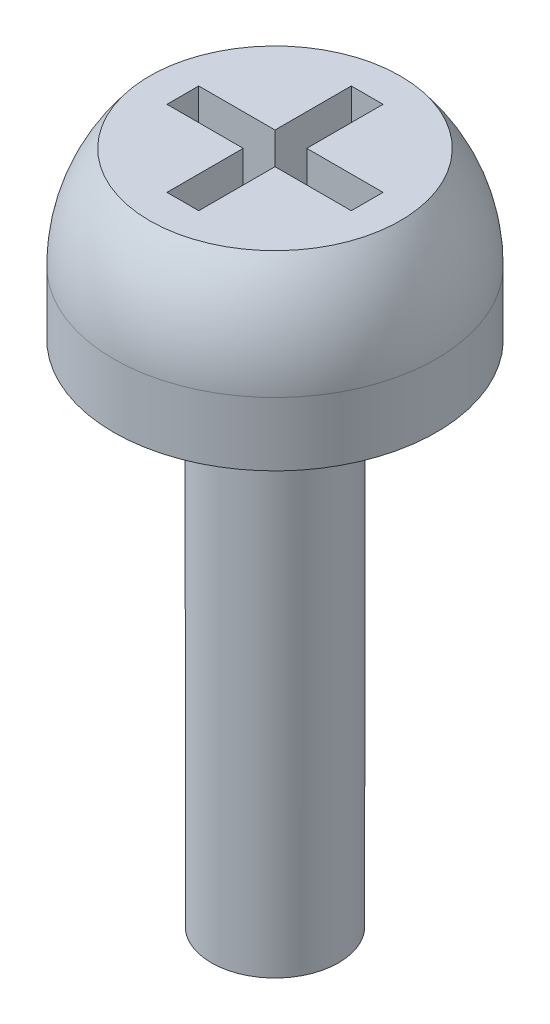
SolidWorks part; units mm, degrees
material "AISI 1020"
ref_plane "Front" through (0, 0, 0) normal (0, 0, 1) x (1, 0, 0)
ref_plane "Top" through (0, 0, 0) normal (0, 1, 0) x (1, 0, 0)
ref_plane "Right" through (0, 0, 0) normal (1, 0, 0) x (0, 0, -1)
sketch "Sketch1" plane through (0, 0, 0) normal (0, 1, 0) x (1, 0, 0)
  circle A0 centre (0, 0) radius 1.27
  dimension "D1" = 2.54
extrude "Boss-Extrude1" add sketch "Sketch1" along normal blind 0.5
ref_plane "Plane1" through (0, 0.5, 0) normal (0, 1, 0) x (1, 0, 0)
sketch "Sketch2" plane through (0, 0.5, 0) normal (0, 1, 0) x (1, 0, 0)
  line L0 (0, 1.27) -> (0, -1.27)
  circle A0 centre (0, 0) radius 1.27 construction
  arc A1 (0, 1.27) -> (0, -1.27) centre (0, 0) ccw
revolve "Revolve1" add sketch "Sketch2" angle 180 about L0
ref_plane "Plane2" through (0, 1.3, 0) normal (0, -1, 0) x (-1, 0, 0)
sketch "Sketch3" plane through (0, 1.3, 0) normal (0, -1, 0) x (-1, 0, 0)
  circle A0 centre (0, 0) radius 2.5
  dimension "D1" = 5
extrude "Cut-Extrude2" cut sketch "Sketch3" against normal blind 1.016
sketch "Sketch5" plane through (0, 1.3, 0) normal (0, -1, 0) x (-1, 0, 0)
  line L0 (0, 0.9864) -> (0, -0.9864) construction
  line L1 (0.9864, 0) -> (-0.9864, 0) construction
  line L2 (0.125, 0.725) -> (0.125, 0.125)
  line L3 (0.125, 0.125) -> (0.725, 0.125)
  line L4 (-0.125, 0.125) -> (-0.725, 0.125)
  line L5 (-0.125, 0.725) -> (-0.125, 0.125)
  line L6 (-0.125, -0.125) -> (-0.725, -0.125)
  line L7 (0.125, -0.125) -> (0.725, -0.125)
  line L8 (0.125, -0.725) -> (0.125, -0.125)
  line L9 (-0.125, -0.725) -> (-0.125, -0.125)
  line L10 (0.125, 0.725) -> (-0.125, 0.725)
  line L11 (0.125, -0.725) -> (-0.125, -0.725)
  line L12 (0.725, 0.125) -> (0.725, -0.125)
  line L13 (-0.725, 0.125) -> (-0.725, -0.125)
  circle A0 centre (0, 0) radius 0.9864 construction
  dimension "D1" = 0.6
  dimension "D2" = 0.125
  dimension "D3" = 0.125
extrude "Cut-Extrude3" cut sketch "Sketch5" along normal blind 1.016
sketch "Sketch6" plane through (0, 0, 0) normal (0, -1, 0) x (-1, 0, 0)
  circle A0 centre (0, 0) radius 0.5
  dimension "D1" = 1
extrude "Boss-Extrude2" add sketch "Sketch6" along normal blind 4
